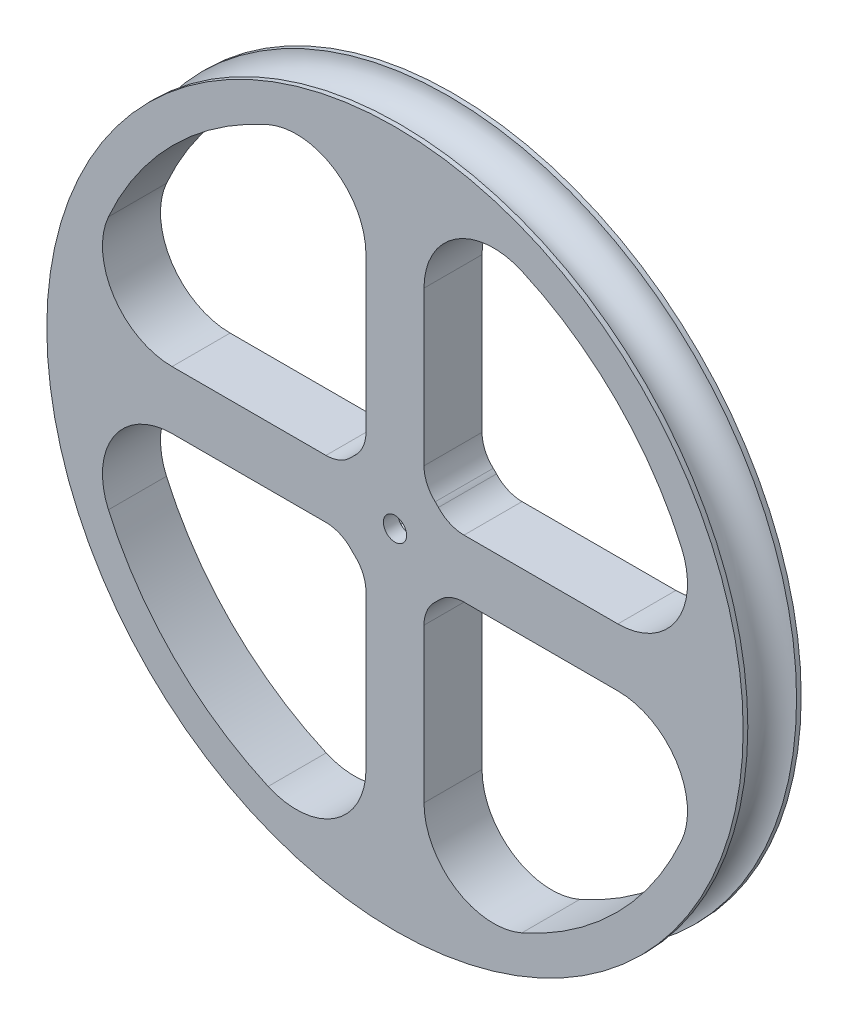
SolidWorks part; units mm, degrees
ref_plane "Front Plane" through (0, 0, 0) normal (0, 0, 1) x (1, 0, 0)
ref_plane "Top Plane" through (0, 0, 0) normal (0, 1, 0) x (1, 0, 0)
ref_plane "Right Plane" through (0, 0, 0) normal (1, 0, 0) x (0, 0, -1)
sketch "Sketch2" plane through (0, 0, 0) normal (0, 1, 0) x (1, 0, 0)
  line L0 (0, 0) -> (34.29, 0) construction
  line L1 (34.29, -3.175) -> (34.29, 3.175)
  line L2 (34.29, 3.175) -> (38.1, 3.175)
  line L3 (34.29, -3.175) -> (38.1, -3.175)
  line L4 (38.1, -3.175) -> (38.1, -2.667)
  line L5 (38.1, 3.175) -> (38.1, 2.667)
  line L6 (38.1, 2.667) -> (37.0609, 2.667) construction
  line L7 (0, -2.667) -> (0, 2.667) construction
  arc A0 (38.1, 2.667) -> (38.1, -2.667) centre (38.1, 0) ccw
  point P6 (34.29, 0)
  point P15 (0, 0)
  dimension "D4" = 2.667
  dimension "D1" = 3.175
  dimension "D2" = 0.508
  dimension "D3" = 0.508
  dimension "D5" = 3.81
  dimension "D6" = 38.1
revolve "Revolve1" add sketch "Sketch2" angle 360 about L7
sketch "Sketch3" plane through (0, 0, 3.175) normal (0, 0, 1) x (1, 0, 0)
  line L0 (0, 34.29) -> (0, -34.29) construction
  line L1 (-34.29, 0) -> (34.29, 0) construction
  line L2 (-34.29, -3.175) -> (34.29, -3.175)
  line L3 (-34.29, 3.175) -> (34.29, 3.175)
  line L4 (-3.175, 34.29) -> (-3.175, -34.29)
  line L5 (3.175, 34.29) -> (3.175, -34.29)
  line L6 (1.9292, 1.8415) -> (-1.9292, 1.8415)
  line L7 (-1.9292, -1.8415) -> (1.9292, -1.8415)
  line L8 (0, 1.8415) -> (0, -1.8415) construction
  circle A0 centre (0, 0) radius 34.29 construction
  circle A1 centre (0, 0) radius 34.29
  circle A2 centre (0, 0) radius 2.667
  circle A3 centre (0, 0) radius 6.477
  circle A4 centre (0, 0) radius 0.127
  point P7 (0, 0)
  point P11 (0, 0)
  circle M10 centre (0, 0) radius 34.29
  dimension "D5" = 5.334
  dimension "D1" = 3.175
  dimension "D6" = 3.683
  dimension "D7" = 3.81
  dimension "D2" = 3.175
  dimension "D3" = 3.175
  dimension "D4" = 3.175
  dimension "D8" = 2.54
extrude "Boss-Extrude1" add sketch "Sketch3" against normal up to surface (6.35 mm away) contours A3 L3 L2 M10 | L3 A3 L2 L4 | L5 A3 L4 L3 | A3 L5 L4 M10 | L4 A3 L3 | L3 A3 L5 | L2 A3 L3 L5 | A3 L2 L3 M10 | A3 L4 L5 M10 | L4 A3 L5 L2 | L2 A3 L4 | L5 A3 L2 | L5 L3 L4 L2 A2 | L6 A2 | L7 A2 up to face at (38.1, 0, -3.175)
fillet "Fillet1" radius 7.62 8 edges at (-3.175, 34.1427, 0) (-3.175, -34.1427, 0) (3.175, 34.1427, 0) (3.175, -34.1427, 0) (34.1427, -3.175, 0) (-34.1427, -3.175, 0) (34.1427, 3.175, 0) (-34.1427, 3.175, 0)
fillet "Fillet2" radius 3.81 8 edges at (5.6454, -3.175, 0) (-5.6454, -3.175, 0) (-3.175, 5.6454, 0) (-3.175, -5.6454, 0) (3.175, 5.6454, 0) (3.175, -5.6454, 0) (5.6454, 3.175, 0) (-5.6454, 3.175, 0)
sketch "Sketch4" plane through (0, 0, 3.175) normal (0, 0, 1) x (1, 0, 0)
  line L0 (1.9292, 1.8415) -> (-1.9292, 1.8415) construction
  line L1 (-1.9292, -1.8415) -> (1.9292, -1.8415) construction
  line L2 (1.9292, 1.8415) -> (-1.9292, 1.8415)
  line L3 (-1.9292, -1.8415) -> (1.9292, -1.8415)
  circle A0 centre (0, 0) radius 1.27
  arc A1 (1.9292, -1.8415) -> (1.9292, 1.8415) centre (0, 0) ccw construction
  arc A2 (-1.9292, 1.8415) -> (-1.9292, -1.8415) centre (0, 0) ccw construction
  arc A3 (1.9292, -1.8415) -> (1.9292, 1.8415) centre (0, 0) ccw
  arc A4 (-1.9292, 1.8415) -> (-1.9292, -1.8415) centre (0, 0) ccw
  dimension "D1" = 2.54
extrude "Boss-Extrude2" add sketch "Sketch4" against normal blind 1.5875 contours A3 L2 A4 L3
